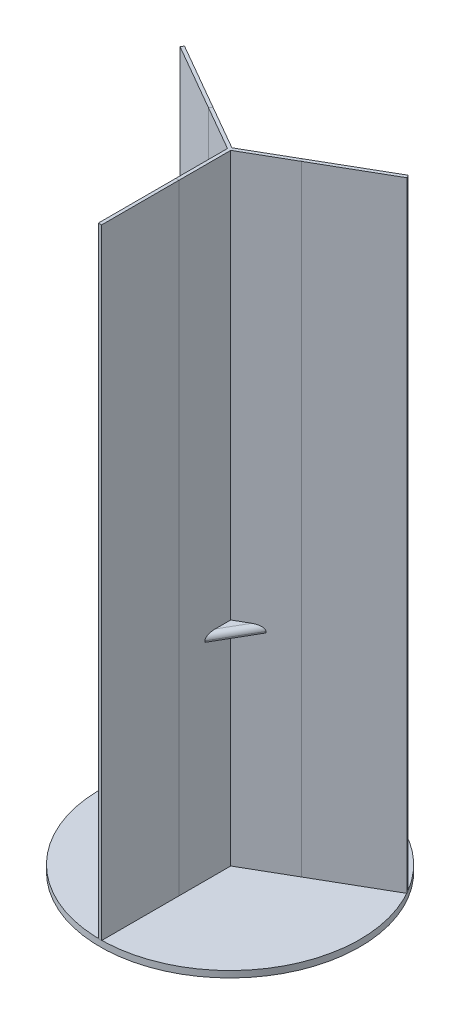
SolidWorks part; units mm, degrees
ref_plane "Front Plane" through (0, 0, 0) normal (0, 0, 1) x (1, 0, 0)
ref_plane "Top Plane" through (0, 0, 0) normal (0, 1, 0) x (1, 0, 0)
ref_plane "Right Plane" through (0, 0, 0) normal (1, 0, 0) x (0, 0, -1)
sketch "Sketch1" plane through (0, 0, 0) normal (0, 1, 0) x (1, 0, 0)
  line L8 (-182.4368, 97.7122) -> (-446.5802, 249.802)
  line L9 (6.3413, -3.681) -> (182.4368, 97.7122)
  line L10 (182.4368, 97.7122) -> (176.0956, 108.7254)
  line L11 (176.0956, 108.7254) -> (0, 7.3322)
  line L12 (-6.3413, -3.681) -> (-6.3413, -206.881)
  line L13 (-6.3413, -206.881) -> (6.3413, -206.881)
  line L14 (6.3413, -206.881) -> (6.3413, -3.681)
  line L15 (-6.3413, -3.681) -> (-182.4368, 97.7122)
  line L16 (-182.4368, 97.7122) -> (-176.0956, 108.7254)
  line L17 (-176.0956, 108.7254) -> (0, 7.3322)
  line L18 (-176.0956, 108.7254) -> (-440.239, 260.8152)
  line L19 (-440.239, 260.8152) -> (-446.5802, 249.802)
  line L20 (-446.5802, 249.802) -> (-182.4368, 97.7122)
  line L21 (182.4368, 97.7122) -> (446.5802, 249.802)
  line L22 (446.5802, 249.802) -> (440.239, 260.8152)
  line L23 (440.239, 260.8152) -> (176.0956, 108.7254)
  line L24 (6.3413, -206.881) -> (6.3413, -511.681)
  line L25 (6.3413, -511.681) -> (-6.3413, -511.681)
  line L26 (-6.3413, -511.681) -> (-6.3413, -206.881)
  line L27 (182.4368, 97.7122) -> (446.5802, 249.802)
  line L28 (176.0956, 108.7254) -> (440.239, 260.8152)
extrude "Boss-Extrude1" add sketch "Sketch1" along normal blind 2438.4 contours L17 L16 L15 L12 L13 L14 L9 L10 L11
sketch "Sketch6" plane through (0, 0, 206.881) normal (0, 0, 1) x (1, 0, 0)
  line L1 (-6.3413, 2438.4) -> (6.3413, 2438.4)
  line L2 (-6.3413, 2438.4) -> (-6.3413, 0)
  line L3 (-6.3413, 0) -> (6.3413, 0)
  line L4 (6.3413, 2438.4) -> (6.3413, 0)
extrude "Boss-Extrude5" add sketch "Sketch6" along normal blind 304.8 separate body
sketch "Sketch7" plane through (179.2662, 0, -103.2188) normal (0.8666, 0, -0.499) x (-0.499, 0, -0.8666)
  line L1 (-6.3542, 2438.4) -> (6.3542, 2438.4)
  line L2 (-6.3542, 2438.4) -> (-6.3542, 0)
  line L3 (-6.3542, 0) -> (6.3542, 0)
  line L4 (6.3542, 2438.4) -> (6.3542, 0)
extrude "Boss-Extrude6" add sketch "Sketch7" along normal blind 304.8 separate body
sketch "Sketch8" plane through (-179.2662, 0, -103.2188) normal (-0.8666, 0, -0.499) x (-0.499, 0, 0.8666)
  line L0 (6.3542, 2438.4) -> (-6.3542, 2438.4) construction
  line L1 (-6.3542, 0) -> (6.3542, 0)
  line L2 (-6.3542, 0) -> (-6.3542, 2438.4)
  line L3 (-6.3542, 2438.4) -> (6.3542, 2438.4)
  line L4 (6.3542, 0) -> (6.3542, 2438.4)
  line L5 (6.3542, 2438.4) -> (6.3542, 0) construction
extrude "Boss-Extrude7" add sketch "Sketch8" along normal blind 304.8 separate body
sketch "Sketch9" plane through (0, 0, 0) normal (0, -1, 0) x (1, 0, 0)
  circle A0 centre (0, 0) radius 510.8387
extrude "Boss-Extrude9" add sketch "Sketch9" along normal blind 25.4 separate body
sketch "Sketch11" plane through (0, 0, 0) normal (0, 1, 0) x (1, 0, 0)
  line L0 (0, 7.3322) -> (88.0478, 58.0288)
  line L1 (176.0956, 108.7254) -> (0, 7.3322) construction
  line L2 (0, 7.3322) -> (-88.0478, 58.0288)
  line L3 (-176.0956, 108.7254) -> (0, 7.3322) construction
  line L4 (-88.0478, 58.0288) -> (88.0478, 58.0288)
extrude "Boss-Extrude14" add sketch "Sketch11" along normal blind 25.4 from offset 812.8
fillet "Fillet1" radius 20.32 1 edges at (0, 838.2, -58.0288)
sketch "Sketch13" plane through (0, 0, 0) normal (0, 1, 0) x (1, 0, 0)
  line L0 (6.3413, -3.681) -> (6.3413, -105.281)
  line L1 (6.3413, -206.881) -> (6.3413, -3.681) construction
  line L2 (6.3413, -3.681) -> (94.3891, 47.0156)
  line L3 (6.3413, -3.681) -> (182.4368, 97.7122) construction
  line L4 (94.3891, 47.0156) -> (6.3413, -105.281)
extrude "Boss-Extrude16" add sketch "Sketch13" along normal blind 25.4 from offset 812.8
fillet "Fillet2" radius 20.32 1 edges at (50.3652, 838.2, 29.1327)
sketch "Sketch14" plane through (0, 0, 0) normal (0, 1, 0) x (1, 0, 0)
  line L0 (-6.3413, -3.681) -> (-94.3891, 47.0156)
  line L1 (-6.3413, -3.681) -> (-182.4368, 97.7122) construction
  line L2 (-6.3413, -3.681) -> (-6.3413, -105.281)
  line L3 (-6.3413, -3.681) -> (-6.3413, -206.881) construction
  line L4 (-6.3413, -105.281) -> (-94.3891, 47.0156)
extrude "Boss-Extrude17" add sketch "Sketch14" along normal blind 25.4 from offset 812.8
fillet "Fillet3" radius 20.32 1 edges at (-50.3652, 838.2, 29.1327)
